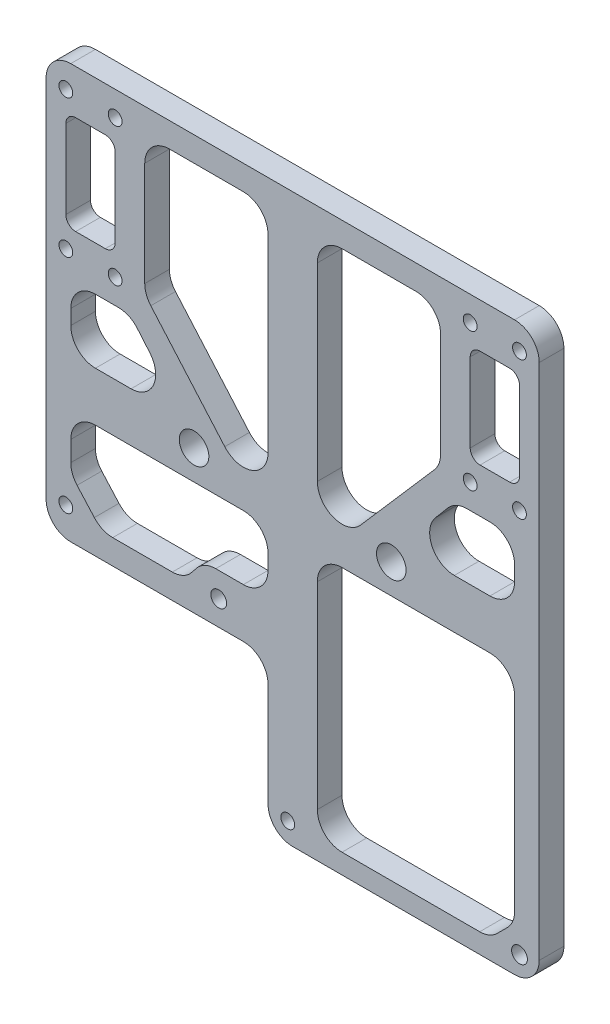
SolidWorks part; units mm, degrees
material "Delrin 2700 NC010, 低粘性ｱｾﾀｰﾙ共重合体 (SS)"
ref_plane "正面" through (0, 0, 0) normal (0, 0, 1) x (1, 0, 0)
ref_plane "平面" through (0, 0, 0) normal (0, 1, 0) x (1, 0, 0)
ref_plane "右側面" through (0, 0, 0) normal (1, 0, 0) x (0, 0, -1)
sketch "ｽｹｯﾁ1" plane through (0, 0, 0) normal (0, 0, 1) x (1, 0, 0)
  line L0 (0, 63.9157) -> (0, -61.5353) construction
  line L1 (-45, 57.5) -> (45, 57.5)
  line L2 (-50, 52.5) -> (-50, -21.5)
  line L3 (0, -57.5) -> (45, -57.5)
  line L4 (50, 52.5) -> (50, -52.5)
  line L5 (-50, 57.5) -> (50, -57.5) construction
  line L6 (-50, -57.5) -> (50, 57.5) construction
  line L7 (-45, -26.5) -> (-10, -26.5)
  line L8 (-5, -31.5) -> (-5, -52.5)
  line L9 (-10, 52.5) -> (-25, 52.5)
  line L10 (-30, 47.5) -> (-30, 26.3699)
  line L11 (-28.773, 23.089) -> (-13.773, 5.839)
  line L12 (-5, 47.5) -> (-5, 9.1199)
  line L13 (-40, 19.5) -> (-35.319, 19.5)
  line L16 (-40, -3.5) -> (-10, -3.5)
  line L17 (-5, -8.5) -> (-5, -11.5)
  line L20 (-45, 14.5) -> (-45, 11.5)
  line L21 (-40, 6.5) -> (-32.7805, 6.5)
  line L22 (-28.9636, 14.7297) -> (-31.5021, 17.7297)
  line L28 (-36.4976, -21.5) -> (-24.4031, -21.5)
  line L30 (-15.5969, -16.5) -> (-10, -16.5)
  line L31 (-45, -12.5886) -> (-45, -8.5)
  line L32 (40, 6.5) -> (32.7805, 6.5)
  line L33 (-44, 48.5) -> (-38, 48.5)
  line L34 (-46, 46.5) -> (-46, 30.5)
  line L35 (-44, 28.5) -> (-38, 28.5)
  line L36 (-36, 46.5) -> (-36, 30.5)
  line L37 (45, 14.5) -> (45, 11.5)
  line L38 (40, 19.5) -> (35.319, 19.5)
  line L39 (28.9636, 14.7297) -> (31.5021, 17.7297)
  line L40 (30, 47.5) -> (30, 26.3699)
  line L41 (10, 52.5) -> (25, 52.5)
  line L42 (5, 47.5) -> (5, 9.1199)
  line L43 (28.773, 23.089) -> (13.773, 5.839)
  line L44 (44, 28.5) -> (38, 28.5)
  line L45 (36, 46.5) -> (36, 30.5)
  line L46 (44, 48.5) -> (38, 48.5)
  line L47 (46, 46.5) -> (46, 30.5)
  line L49 (10, -3.5) -> (40, -3.5)
  line L52 (45, -8.5) -> (45, -46.4289)
  line L53 (37.9289, -53.5) -> (10, -53.5)
  line L55 (5, -8.5) -> (5, -48.5)
  line L56 (43.5355, -49.9645) -> (41.4645, -52.0355)
  line L57 (-19.5012, -18.3765) -> (-20.4988, -19.6235)
  line L58 (-40.2225, -19.8354) -> (-43.7249, -15.924)
  circle A0 centre (-46, 52.5) radius 1.4
  circle A1 centre (-36, 52.5) radius 1.4
  circle A2 centre (-46, 24.5) radius 1.4
  circle A3 centre (-36, 24.5) radius 1.4
  circle A8 centre (46, 24.5) radius 1.4
  circle A9 centre (36, 24.5) radius 1.4
  circle A10 centre (36, 52.5) radius 1.4
  circle A11 centre (46, 52.5) radius 1.4
  circle A12 centre (-20, 2.5) radius 3
  circle A13 centre (20, 2.5) radius 3
  circle A14 centre (-1, -53.5) radius 1.4
  circle A15 centre (-46, -20.5) radius 1.4
  circle A16 centre (46, -53.5) radius 1.6
  circle A17 centre (-15, -21.5) radius 1.6
  arc A18 (-5, -31.5) -> (-10, -26.5) centre (-10, -31.5) ccw
  arc A19 (-45, -26.5) -> (-50, -21.5) centre (-45, -21.5) cw
  arc A20 (-50, 52.5) -> (-45, 57.5) centre (-45, 52.5) cw
  arc A21 (45, 57.5) -> (50, 52.5) centre (45, 52.5) cw
  arc A22 (50, -52.5) -> (45, -57.5) centre (45, -52.5) cw
  arc A23 (0, -57.5) -> (-5, -52.5) centre (0, -52.5) cw
  arc A24 (-30, 26.3699) -> (-28.773, 23.089) centre (-25, 26.3699) ccw
  arc A25 (-13.773, 5.839) -> (-5, 9.1199) centre (-10, 9.1199) ccw
  arc A26 (-5, 47.5) -> (-10, 52.5) centre (-10, 47.5) ccw
  arc A27 (-25, 52.5) -> (-30, 47.5) centre (-25, 47.5) ccw
  arc A28 (-45, 11.5) -> (-40, 6.5) centre (-40, 11.5) ccw
  arc A29 (-32.7805, 6.5) -> (-28.9636, 14.7297) centre (-32.7805, 11.5) ccw
  arc A30 (-31.5021, 17.7297) -> (-35.319, 19.5) centre (-35.319, 14.5) ccw
  arc A31 (-40, 19.5) -> (-45, 14.5) centre (-40, 14.5) ccw
  arc A37 (-10, -16.5) -> (-5, -11.5) centre (-10, -11.5) ccw
  arc A38 (-5, -8.5) -> (-10, -3.5) centre (-10, -8.5) ccw
  arc A39 (-40, -3.5) -> (-45, -8.5) centre (-40, -8.5) ccw
  arc A40 (-46, 30.5) -> (-44, 28.5) centre (-44, 30.5) ccw
  arc A41 (-38, 28.5) -> (-36, 30.5) centre (-38, 30.5) ccw
  arc A42 (-36, 46.5) -> (-38, 48.5) centre (-38, 46.5) ccw
  arc A43 (-44, 48.5) -> (-46, 46.5) centre (-44, 46.5) ccw
  arc A44 (45, 11.5) -> (40, 6.5) centre (40, 11.5) cw
  arc A45 (40, 19.5) -> (45, 14.5) centre (40, 14.5) cw
  arc A46 (32.7805, 6.5) -> (28.9636, 14.7297) centre (32.7805, 11.5) cw
  arc A47 (31.5021, 17.7297) -> (35.319, 19.5) centre (35.319, 14.5) cw
  arc A48 (25, 52.5) -> (30, 47.5) centre (25, 47.5) cw
  arc A49 (5, 47.5) -> (10, 52.5) centre (10, 47.5) cw
  arc A50 (30, 26.3699) -> (28.773, 23.089) centre (25, 26.3699) cw
  arc A51 (13.773, 5.839) -> (5, 9.1199) centre (10, 9.1199) cw
  arc A52 (38, 28.5) -> (36, 30.5) centre (38, 30.5) cw
  arc A53 (36, 46.5) -> (38, 48.5) centre (38, 46.5) cw
  arc A54 (46, 30.5) -> (44, 28.5) centre (44, 30.5) cw
  arc A55 (44, 48.5) -> (46, 46.5) centre (44, 46.5) cw
  arc A56 (45, -8.5) -> (40, -3.5) centre (40, -8.5) ccw
  arc A57 (10, -3.5) -> (5, -8.5) centre (10, -8.5) ccw
  arc A58 (5, -48.5) -> (10, -53.5) centre (10, -48.5) ccw
  arc A59 (45, -46.4289) -> (43.5355, -49.9645) centre (40, -46.4289) cw
  arc A60 (41.4645, -52.0355) -> (37.9289, -53.5) centre (37.9289, -48.5) cw
  arc A61 (-15.5969, -16.5) -> (-19.5012, -18.3765) centre (-15.5969, -21.5) ccw
  arc A62 (-20.4988, -19.6235) -> (-24.4031, -21.5) centre (-24.4031, -16.5) cw
  arc A63 (-36.4976, -21.5) -> (-40.2225, -19.8354) centre (-36.4976, -16.5) cw
  arc A64 (-43.7249, -15.924) -> (-45, -12.5886) centre (-40, -12.5886) cw
  point P0 (0, 0)
  point P60 (-30, 24.5)
  point P65 (-5, 52.5)
  point P68 (-30, 52.5)
  point P78 (-45, 6.5)
  point P81 (-22, 6.5)
  point P84 (-33, 19.5)
  point P87 (-45, 19.5)
  point P97 (-38.732, -21.5)
  point P101 (-45, -14.5)
  point P105 (-5, -16.5)
  point P108 (-5, -3.5)
  point P117 (-46, 28.5)
  point P122 (-36, 48.5)
  point P125 (-46, 48.5)
  point P170 (45, -3.5)
  point P173 (5, -3.5)
  point P176 (5, -53.5)
  point P178 (45, -48.5)
  point P181 (40, -53.5)
  dimension "D3" = 2.8
  dimension "D4" = 2.8
  dimension "D5" = 2.8
  dimension "D6" = 2.8
  dimension "D7" = 10
  dimension "D8" = 10
  dimension "D9" = 4
  dimension "D10" = 4
  dimension "D11" = 28
  dimension "D12" = 5
  dimension "D13" = 28
  dimension "D14" = 5
  dimension "D15" = 6
  dimension "D16" = 6
  dimension "D17" = 40
  dimension "D18" = 20
  dimension "D19" = 60
  dimension "D20" = 60
  dimension "D21" = 2.8
  dimension "D22" = 2.8
  dimension "D23" = 45
  dimension "D24" = 33
  dimension "D25" = 4
  dimension "D26" = 4
  dimension "D27" = 3.2
  dimension "D28" = 3.2
  dimension "D29" = 61
  dimension "D30" = 32
  dimension "D31" = 4
  dimension "D32" = 4
  dimension "D36" = 5
  dimension "D39" = 5
  dimension "D46" = 5
  dimension "D47" = 5
  dimension "D53" = 20
  dimension "D57" = 2
  dimension "D63" = 5
  dimension "D60" = 5
  dimension "D1" = 100
  dimension "D2" = 115
  dimension "D33" = 84
  dimension "D34" = 55
  dimension "D35" = 50
  dimension "D37" = 28
  dimension "D38" = 25
  dimension "D40" = 5
  dimension "D41" = 12
  dimension "D42" = 5
  dimension "D43" = 13
  dimension "D44" = 23
  dimension "D45" = 13
  dimension "D48" = 40
  dimension "D49" = 5
  dimension "D50" = 18
  dimension "D51" = 6.268
  dimension "D52" = 7
  dimension "D54" = 10
  dimension "D55" = 4
  dimension "D56" = 9
  dimension "D58" = 40
  dimension "D59" = 45
  dimension "D61" = 32.9289
  dimension "D62" = 5
  dimension "D64" = 50
extrude "ﾎﾞｽ - 押し出し1" add sketch "ｽｹｯﾁ1" along normal blind 5 contours L4 L1 L2 L3 A10 A8 A3 A2 A1 A0 A9 A11
